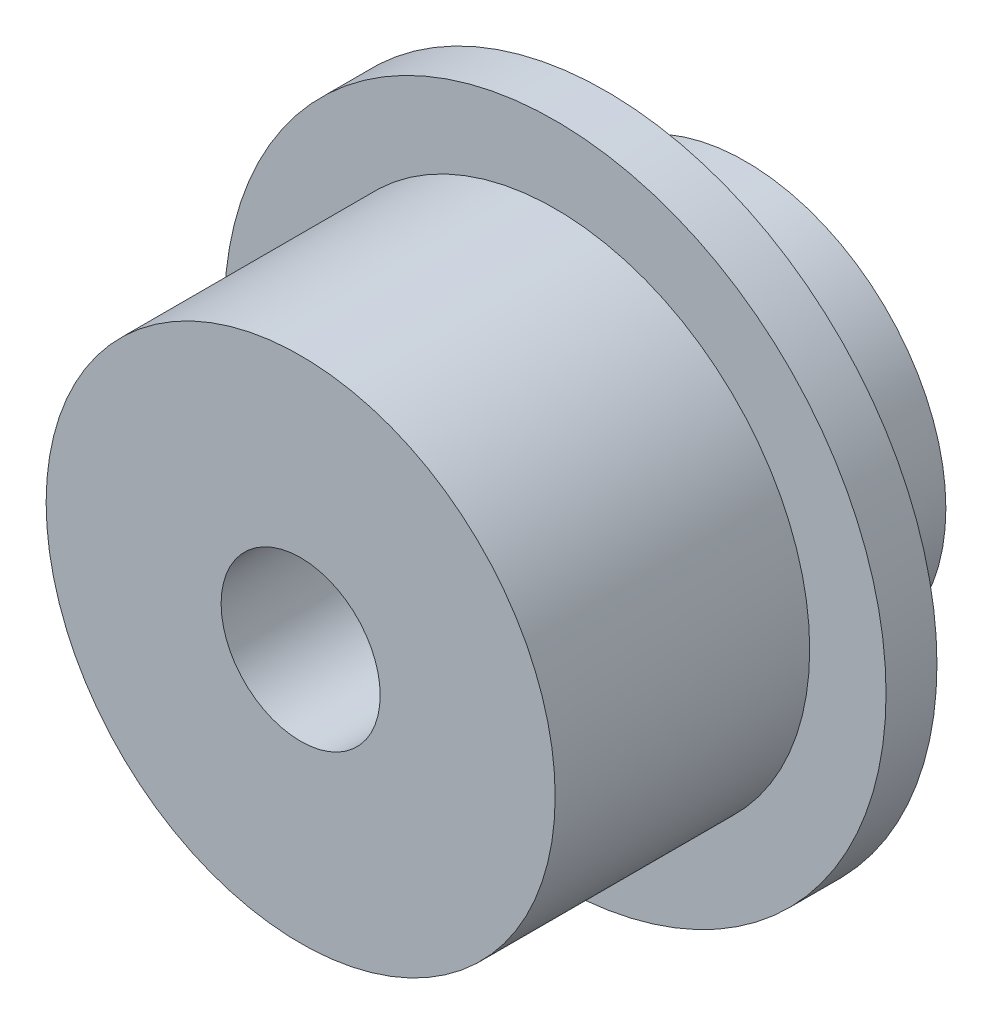
SolidWorks part; units mm, degrees
ref_plane "Front" through (0, 0, 0) normal (0, 0, 1) x (1, 0, 0)
ref_plane "Top" through (0, 0, 0) normal (0, 1, 0) x (1, 0, 0)
ref_plane "Right" through (0, 0, 0) normal (1, 0, 0) x (0, 0, -1)
sketch "Sketch1" plane through (0, 0, 0) normal (0, 0, 1) x (1, 0, 0)
  circle A0 centre (0, 0) radius 9.9949
  dimension "D1" = 19.9898
extrude "Boss-Extrude1" add sketch "Sketch1" along normal blind 6.9596
sketch "Sketch2" plane through (0, 0, 6.9596) normal (0, 0, 1) x (1, 0, 0)
  circle A0 centre (0, 0) radius 16.51
  dimension "D1" = 33.02
extrude "Boss-Extrude2" add sketch "Sketch2" along normal blind 2.54
sketch "Sketch5" plane through (0, 0, 9.4996) normal (0, 0, 1) x (1, 0, 0)
  circle A0 centre (0, 0) radius 12.7
  dimension "D1" = 25.4
extrude "Boss-Extrude4" add sketch "Sketch5" along normal blind 12.7
sketch "Sketch6" plane through (0, 0, 0) normal (0, 0, -1) x (-1, 0, 0)
  circle A0 centre (0, 0) radius 3.9688
  dimension "D1" = 7.9375
extrude "Cut-Extrude1" cut sketch "Sketch6" against normal up to surface (22.1996 mm away) up to face at (12.7, 0, 22.1996)
